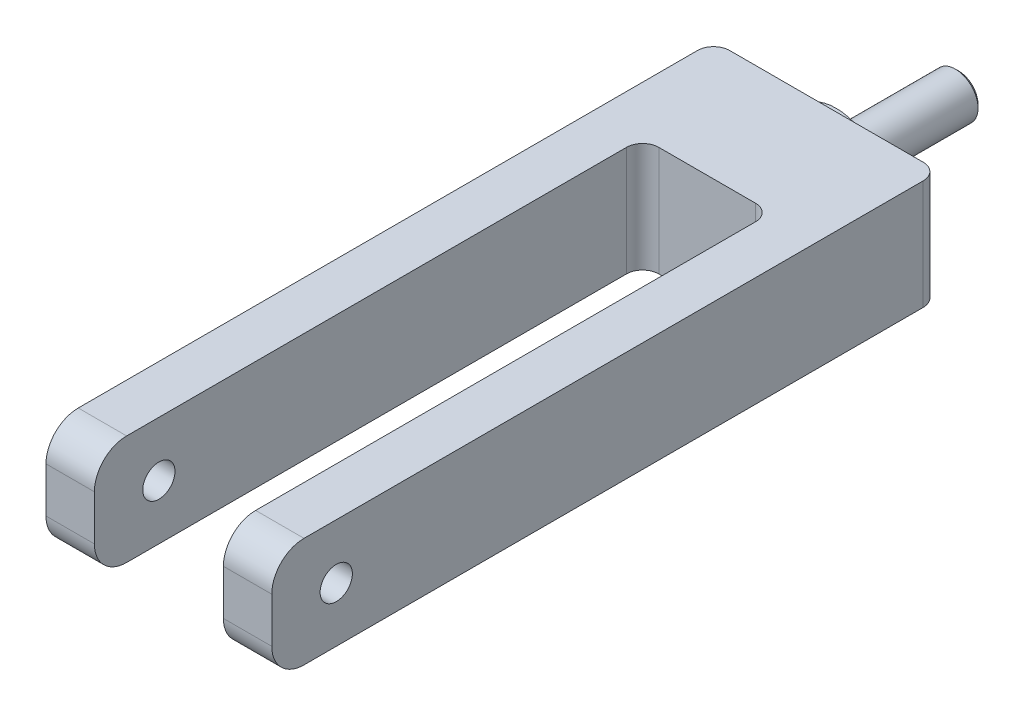
SolidWorks part; units mm, degrees
ref_plane "前视基准面" through (0, 0, 0) normal (0, 0, 1) x (1, 0, 0)
ref_plane "上视基准面" through (0, 0, 0) normal (0, 1, 0) x (1, 0, 0)
ref_plane "右视基准面" through (0, 0, 0) normal (1, 0, 0) x (0, 0, -1)
sketch "草图1" plane through (0, 0, 0) normal (0, 1, 0) x (1, 0, 0)
  line L0 (20, -87.0937) -> (35, -87.0937)
  line L1 (-35, 119.9063) -> (35, 119.9063)
  line L2 (-35, 119.9063) -> (-35, -87.0937)
  line L3 (-35, -87.0937) -> (-20, -87.0937)
  line L4 (35, 119.9063) -> (35, -87.0937)
  line L5 (-20, 82.9063) -> (20, 82.9063)
  line L6 (-20, 82.9063) -> (-20, -87.0937)
  line L7 (0, 0) -> (0, -80.9008) construction
  line L8 (20, 82.9063) -> (20, -87.0937)
  line L9 (0, -55) -> (0, 55) construction
  dimension "D1" = 207
  dimension "D2" = 170
  dimension "D3" = 40
  dimension "D4" = 70
extrude "凸台-拉伸1" add sketch "草图1" along normal mid plane 34
fillet "圆角1" radius 5 4 edges at (20, 0, -82.9063) (-20, 0, -82.9063) (35, 0, -119.9063) (-35, 0, -119.9063)
sketch "草图2" plane through (0, 0, -119.9063) normal (0, 0, -1) x (-1, 0, 0)
  circle A0 centre (0, 0) radius 15
  dimension "D1" = 30
extrude "凸台-拉伸2" add sketch "草图2" along normal blind 3
sketch "草图4" plane through (0, 0, 0) normal (1, 0, 0) x (0, 0, -1)
  line L1 (-87.0937, 17) -> (-87.0937, -17) construction
  line L4 (-98.6029, 0) -> (-22.6374, 0) construction
  line L5 (-87.0937, 17) -> (114.9063, 17) construction
  line L6 (-87.0937, -17) -> (114.9063, -17) construction
  circle A0 centre (-67.0937, 0) radius 5
  dimension "D1" = 20
extrude "切除-拉伸1" cut sketch "草图4" against normal mid plane 112
sketch "草图3" plane through (0, 0, -122.9063) normal (0, 0, -1) x (-1, 0, 0)
  circle A0 centre (0, 0) radius 7
  dimension "D1" = 14
extrude "凸台-拉伸3" add sketch "草图3" along normal blind 38
cosmetic thread "装饰螺纹线2" parameters "D1"=15.5, "D2"=12.376
fillet "圆角2" radius 10 4 edges at (27.5, -17, 87.0937) (-27.5, -17, 87.0937) (-27.5, 17, 87.0937) (27.5, 17, 87.0937)
chamfer "倒角1" distance 1 angle 45 1 edges at (-7, 0, -160.9063)
